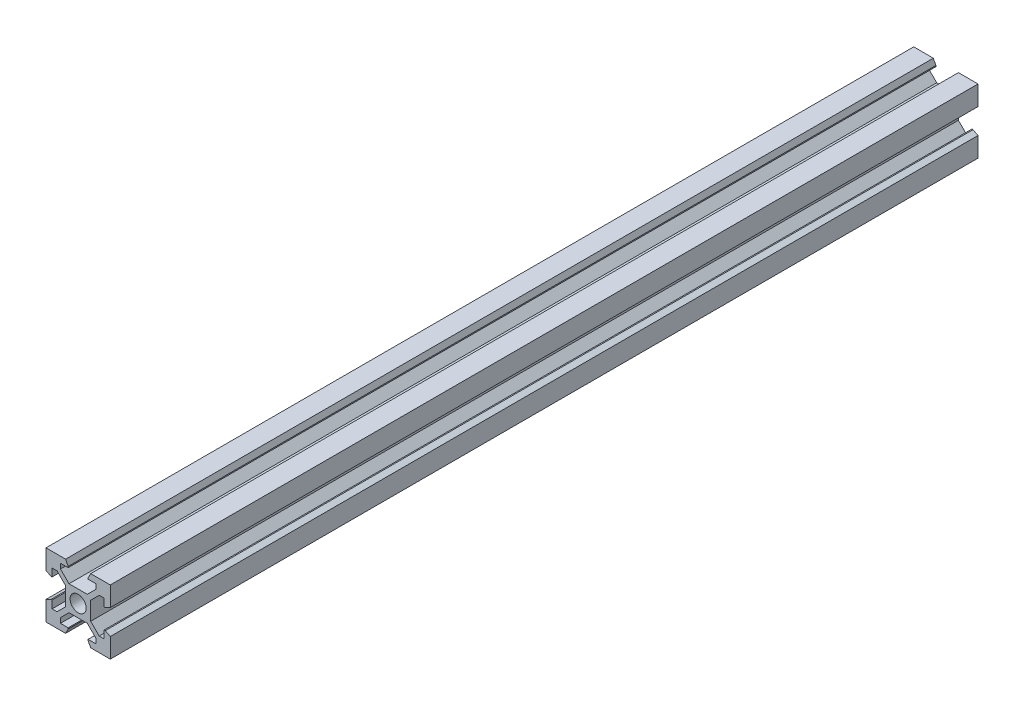
SolidWorks part; units mm, degrees
ref_plane "Front Plane" through (0, 0, 0) normal (0, 0, 1) x (1, 0, 0)
ref_plane "Top Plane" through (0, 0, 0) normal (0, 1, 0) x (1, 0, 0)
ref_plane "Right Plane" through (0, 0, 0) normal (1, 0, 0) x (0, 0, -1)
sketch "Sketch1" plane through (0, 0, 0) normal (0, 0, 1) x (1, 0, 0)
  line L0 (0, 20) -> (0, 13.8958)
  line L1 (0, 0) -> (20, 0)
  line L2 (0, 0) -> (0, 20)
  line L3 (0, 20) -> (20, 20)
  line L4 (20, 0) -> (20, 20)
  line L5 (0, 13.8958) -> (1.56, 13.1)
  line L6 (1.56, 13.1) -> (1.9, 13.1)
  line L7 (1.9, 13.1) -> (1.9, 15.5)
  line L8 (1.9, 15.5) -> (3.4393, 15.5)
  line L9 (3.4393, 15.5) -> (6.2656, 12.6737)
  line L10 (6.2656, 12.6737) -> (7.3263, 13.7344)
  line L11 (7.3263, 13.7344) -> (4.5, 16.5607)
  line L12 (4.5, 16.5607) -> (4.5, 18.1)
  line L13 (4.5, 18.1) -> (6.9, 18.1)
  line L14 (6.9, 18.1) -> (6.9, 18.44)
  line L15 (6.9, 18.44) -> (6.1, 20)
  line L16 (6.1, 20) -> (0, 20)
  line L17 (10, 10) -> (6.1, 13.9)
  line L18 (6.1, 6.1) -> (13.9, 6.1)
  line L19 (6.1, 6.1) -> (6.1, 13.9)
  line L20 (6.1, 13.9) -> (13.9, 13.9)
  line L21 (13.9, 6.1) -> (13.9, 13.9)
  line L22 (6.796, 13.204) -> (4.0494, 15.9506)
  line L23 (10, 10) -> (10, 24.9145) construction
  line L24 (13.1, 18.44) -> (13.9, 20)
  line L25 (13.1, 18.1) -> (13.1, 18.44)
  line L26 (15.5, 18.1) -> (13.1, 18.1)
  line L27 (15.5, 16.5607) -> (15.5, 18.1)
  line L28 (12.6737, 13.7344) -> (15.5, 16.5607)
  line L29 (13.7344, 12.6737) -> (12.6737, 13.7344)
  line L30 (16.5607, 15.5) -> (13.7344, 12.6737)
  line L31 (18.1, 15.5) -> (16.5607, 15.5)
  line L32 (18.1, 13.1) -> (18.1, 15.5)
  line L33 (18.44, 13.1) -> (18.1, 13.1)
  line L34 (20, 13.8958) -> (18.44, 13.1)
  line L35 (10, 10) -> (22.1718, 10)
  line L36 (20, 6.1042) -> (18.44, 6.9)
  line L37 (18.44, 6.9) -> (18.1, 6.9)
  line L38 (18.1, 6.9) -> (18.1, 4.5)
  line L39 (18.1, 4.5) -> (16.5607, 4.5)
  line L40 (16.5607, 4.5) -> (13.7344, 7.3263)
  line L41 (13.7344, 7.3263) -> (12.6737, 6.2656)
  line L42 (12.6737, 6.2656) -> (15.5, 3.4393)
  line L43 (15.5, 3.4393) -> (15.5, 1.9)
  line L44 (15.5, 1.9) -> (13.1, 1.9)
  line L45 (13.1, 1.9) -> (13.1, 1.56)
  line L46 (13.1, 1.56) -> (13.9, 0)
  line L47 (6.9, 1.56) -> (6.1, 0)
  line L48 (6.9, 1.9) -> (6.9, 1.56)
  line L49 (4.5, 1.9) -> (6.9, 1.9)
  line L50 (4.5, 3.4393) -> (4.5, 1.9)
  line L51 (7.3263, 6.2656) -> (4.5, 3.4393)
  line L52 (6.2656, 7.3263) -> (7.3263, 6.2656)
  line L53 (3.4393, 4.5) -> (6.2656, 7.3263)
  line L54 (1.9, 4.5) -> (3.4393, 4.5)
  line L55 (1.9, 6.9) -> (1.9, 4.5)
  line L56 (1.56, 6.9) -> (1.9, 6.9)
  line L57 (0, 6.1042) -> (1.56, 6.9)
  circle A0 centre (10, 10) radius 2.5
  point P21 (2.6697, 15.5)
  dimension "D3" = 5
  dimension "D1" = 20
  dimension "D2" = 20
  dimension "D4" = 10
  dimension "D5" = 10
  dimension "D6" = 7.8
  dimension "D7" = 7.8
  dimension "D8" = 6.1
  dimension "D9" = 6.1
  dimension "D10" = 6.9
  dimension "D11" = 6.9
  dimension "D12" = 6.1042
  dimension "D13" = 6.1
  dimension "D14" = 0.34
  dimension "D15" = 0.34
  dimension "D16" = 1.9
  dimension "D17" = 4.5
  dimension "D18" = 4.5
  dimension "D19" = 1.5
  dimension "D20" = 1.9
extrude "Boss-Extrude1" add sketch "Sketch1" along normal blind 270
